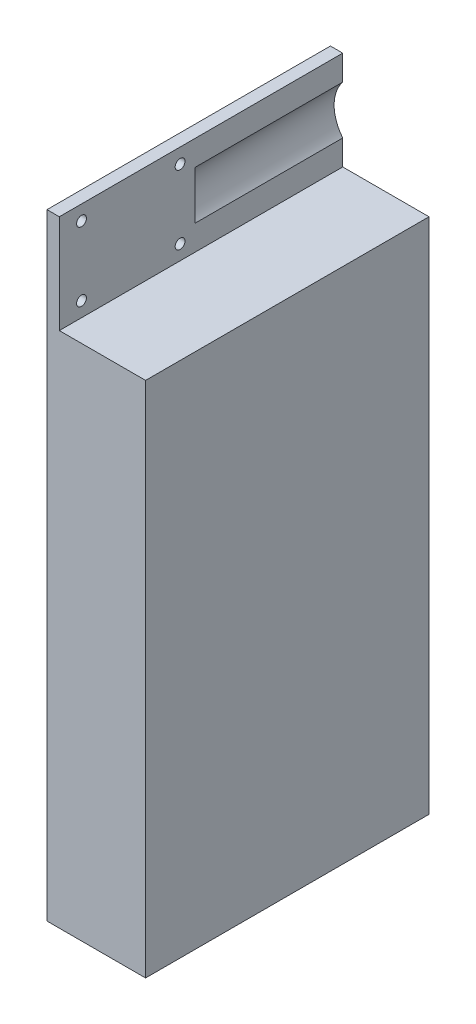
SolidWorks part; units mm, degrees
ref_plane "Front Plane" through (0, 0, 0) normal (0, 0, 1) x (1, 0, 0)
ref_plane "Top Plane" through (0, 0, 0) normal (0, 1, 0) x (1, 0, 0)
ref_plane "Right Plane" through (0, 0, 0) normal (1, 0, 0) x (0, 0, -1)
sketch "Sketch1" plane through (0, 0, 0) normal (0, 0, 1) x (1, 0, 0)
  line L0 (0, 0) -> (0, 40)
  line L1 (0, 40) -> (-5, 40)
  line L2 (-5, 40) -> (-5, -210)
  line L3 (-5, -210) -> (35, -210)
  line L4 (35, -210) -> (35, 0)
  line L5 (0, 0) -> (35, 0)
  dimension "D1" = 5
  dimension "D2" = 40
  dimension "D3" = 250
  dimension "D4" = 35
extrude "Boss-Extrude1" add sketch "Sketch1" along normal blind 115
sketch "Sketch2" plane through (-5, 0, 0) normal (-1, 0, 0) x (0, 0, 1)
  line L0 (106, 40) -> (106, 34) construction
  line L1 (115, 40) -> (0, 40) construction
  line L2 (115, 40) -> (115, -210) construction
  line L3 (106, 34) -> (66, 34) construction
  line L4 (106, 34) -> (106, 20) construction
  line L5 (106, 20) -> (115, 20) construction
  circle A0 centre (106, 34) radius 2
  circle A1 centre (66, 34) radius 2
  circle A2 centre (66, 6) radius 2
  circle A3 centre (106, 6) radius 2
  dimension "D4" = 4
  dimension "D5" = 4
  dimension "D1" = 6
  dimension "D2" = 9
  dimension "D3" = 40
  dimension "D6" = 28
extrude "Cut-Extrude1" cut sketch "Sketch2" against normal through all
sketch "Sketch3" plane through (0, 0, 0) normal (0, 0, -1) x (-1, 0, 0)
  line L0 (0, 36) -> (0, 32) construction
  line L2 (0, 40) -> (5, 40) construction
  circle A0 centre (-12, 20) radius 15.5
  point P6 (-7.7526, 29.7132)
  dimension "D3" = 31
  dimension "D1" = 12
  dimension "D2" = 20
extrude "Cut-Extrude2" cut sketch "Sketch3" against normal blind 60
